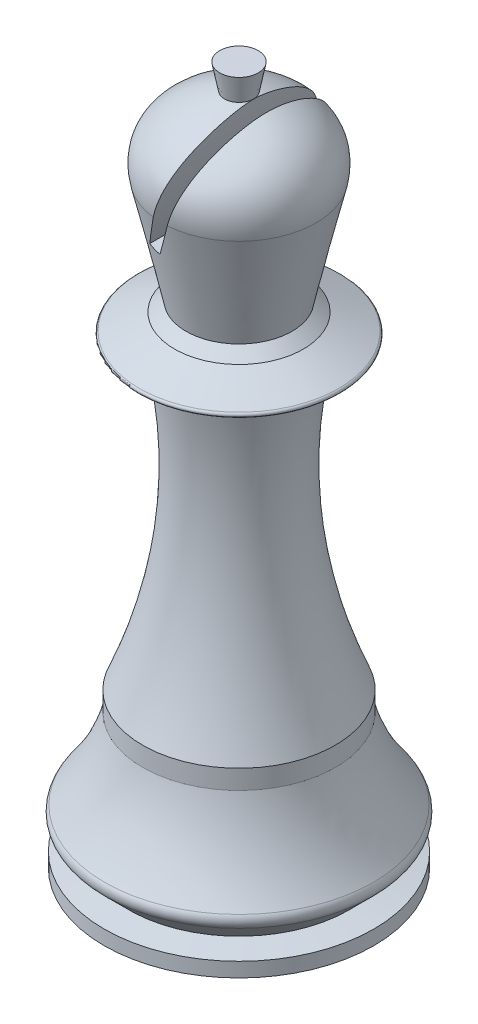
SolidWorks part; units mm, degrees
material "Maple"
ref_plane "Front Plane" through (0, 0, 0) normal (0, 0, 1) x (1, 0, 0)
ref_plane "Top Plane" through (0, 0, 0) normal (0, 1, 0) x (1, 0, 0)
ref_plane "Right Plane" through (0, 0, 0) normal (1, 0, 0) x (0, 0, -1)
sketch "Sketch3" plane through (0, 0, 0) normal (0, 0, 1) x (1, 0, 0)
  line L0 (0, 0) -> (0, 50)
  line L1 (0, 0) -> (12, 0)
  line L2 (12, 0) -> (12, 3.0957) construction
  line L3 (0, 36) -> (9, 36) construction
  line L4 (9, 36) -> (9, 32.5) construction
  line L5 (9, 32.5) -> (0, 32.5) construction
  line L6 (12, 0) -> (12, 1.5)
  line L7 (12, 1.5) -> (9.8747, 1.8747)
  line L8 (0, 43) -> (3.5, 36.9378) construction
  line L9 (11, 33.5) -> (5, 32.5)
  line L10 (7, 14) -> (7, 16)
  line L11 (9.8747, 1.8747) -> (13, 5)
  line L12 (12, 3.0957) -> (12, 0) construction
  line L13 (3.5, 36.9378) -> (4.6918, 35.9378)
  line L14 (4.6918, 35.9378) -> (11, 33.5)
  arc A0 (0, 50) -> (0, 36) centre (0, 43) cw construction
  arc A1 (0, 50) -> (3.5, 36.9378) centre (0, 43) cw
  spline S0 degree 2 poles (12, 3.0957) (2.5166, 14.8814) (5, 32.5) knots 0 0 0 1 1 1 construction
  spline S1 degree 2 poles (7, 14) (9.1788, 9.005) (13, 5) knots 0 0 0 1 1 1
  spline S2 degree 3 poles (5, 32.5) (4.6326, 30.3602) (4.7601, 24.4105) (5.3037, 19.8693) (7, 16) knots 0 0 0 0 0.393038 1 1 1 1
  dimension "D10" = 31.1369
  dimension "D1" = 12
  dimension "D2" = 50
  dimension "D3" = 14
  dimension "D4" = 3.5
  dimension "D5" = 100
  dimension "D6" = 30
  dimension "D7" = 1.5
  dimension "D8" = 5
  dimension "D9" = 1
  dimension "D11" = 2
  dimension "D12" = 14
  dimension "D13" = 55
  dimension "D14" = 1
  dimension "D15" = 5
  dimension "D16" = 3.0957
  dimension "D17" = 7
  dimension "D18" = 1
  dimension "D19" = 40
  dimension "D20" = 11
sketch "Sketch2" plane through (0, 0, 0) normal (0, 0, 1) x (1, 0, 0)
  line L0 (0, -0.0296) -> (14, -0.0296)
  line L1 (0, -0.0296) -> (0, 55) construction
  line L2 (0, 69.9704) -> (8, 69.9704) construction
  line L3 (14, -0.0296) -> (14, 1.4704)
  line L4 (14, 1.4704) -> (11.4497, 1.9201)
  line L5 (11.4497, 1.9201) -> (14.5, 4.9704)
  line L6 (8, 69.9704) -> (8, 50) construction
  line L7 (0, 69.9704) -> (0, -0.0296)
  line L8 (10, 16) -> (10, 14)
  line L9 (0, 14) -> (10, 14) construction
  line L10 (7, 46.9704) -> (0, 46.9704) construction
  line L13 (0, 61.9704) -> (8, 61.9704) construction
  line L17 (0, 69.9704) -> (0, 72.4704)
  line L18 (0, 72.4704) -> (2, 72.4704)
  line L19 (2, 72.4704) -> (1.5, 69.8668)
  line L20 (11, 47.9704) -> (7, 46.9704)
  line L21 (5.5, 50.9704) -> (6.6918, 49.9704)
  line L22 (6.6918, 49.9704) -> (11, 47.9704)
  line L23 (0, 49.9704) -> (11, 49.9704) construction
  line L24 (11, 49.9704) -> (11, 46.9704) construction
  line L25 (7, 46.9704) -> (11, 46.9704) construction
  spline S0 degree 3 poles (0, 69.9704) (2.5196, 69.9704) (6.2446, 68.4001) (8.4926, 64.3047) (8, 61.9704) knots 0 0 0 0 0.509944 1 1 1 1 construction
  spline S1 degree 2 poles (10, 14) (11.2031, 8.9824) (14.5, 4.9704) knots 0 0 0 1 1 1
  spline S2 degree 2 poles (7, 46.9704) (3.7057, 31.3766) (10, 16) knots 0 0 0 1 1 1
  spline S3 degree 3 poles (1.5, 69.8668) (4.8312, 68.8517) (9.0082, 66.7482) (8, 61.9704) knots 0 0 0 0 1 1 1 1
  spline S4 degree 2 poles (8, 61.9704) (5.86, 54.6475) (6, 46.9704) knots 0 0 0 1 1 1 construction
  spline S5 degree 2 poles (8, 61.9704) (6.6777, 56.4868) (5.5, 50.9704) knots 0 0 0 1 1 1
  dimension "D1" = 14
  dimension "D2" = 1.5
  dimension "D3" = 0.5
  dimension "D4" = 55
  dimension "D5" = 5
  dimension "D6" = 100
  dimension "D9" = 8
  dimension "D11" = 7
  dimension "D7" = 8
  dimension "D10" = 2.5
  dimension "D12" = 2
  dimension "D13" = 1
  dimension "D14" = 1.5
  dimension "D15" = 10
  dimension "D8" = 11
  dimension "D16" = 70
  dimension "D18" = 3
  dimension "D19" = 1
  dimension "D20" = 1
  dimension "D17" = 11
  dimension "D21" = 47
  dimension "D23" = 14.0296
revolve "Revolve1" add sketch "Sketch2" angle 360 about L7
fillet "Fillet1" radius 1 1 edges at (-14.5, 4.9704, 0)
fillet "Fillet2" radius 0.25 1 edges at (-11, 47.9704, 0)
sketch "Sketch5" plane through (0, 0, 0) normal (0, 0, 1) x (1, 0, 0)
  line L0 (0, 0) -> (0, 75.1193) construction
  line L1 (2.3, 70) -> (-2, 58) construction
  line L2 (0, 58) -> (-2, 58) construction
  line L3 (2.3, 70) -> (0, 70) construction
  line L4 (-2.75, 58) -> (-1.25, 58)
  line L5 (1.55, 70) -> (3.05, 70)
  spline S0 degree 2 poles (3.05, 70) (1.6096, 63.7315) (-1.25, 58) knots 0 0 0 1 1 1
  spline S1 degree 2 poles (1.55, 70) (0.1125, 63.7395) (-2.75, 58) knots 0 0 0 1 1 1
  point P10 (-2, 58)
  point P13 (2.3, 70)
  dimension "D1" = 58
  dimension "D2" = 2.3
  dimension "D3" = 70
  dimension "D4" = 1.5
  dimension "D5" = 1.5
  dimension "D6" = 2
extrude "Cut-Extrude1" cut sketch "Sketch5" against normal mid plane 20
equation "\"height\"= 70mm"
equation "\"baseRadius\"= 14mm"
equation "\"D1@Sketch2\"=\"baseRadius\""
